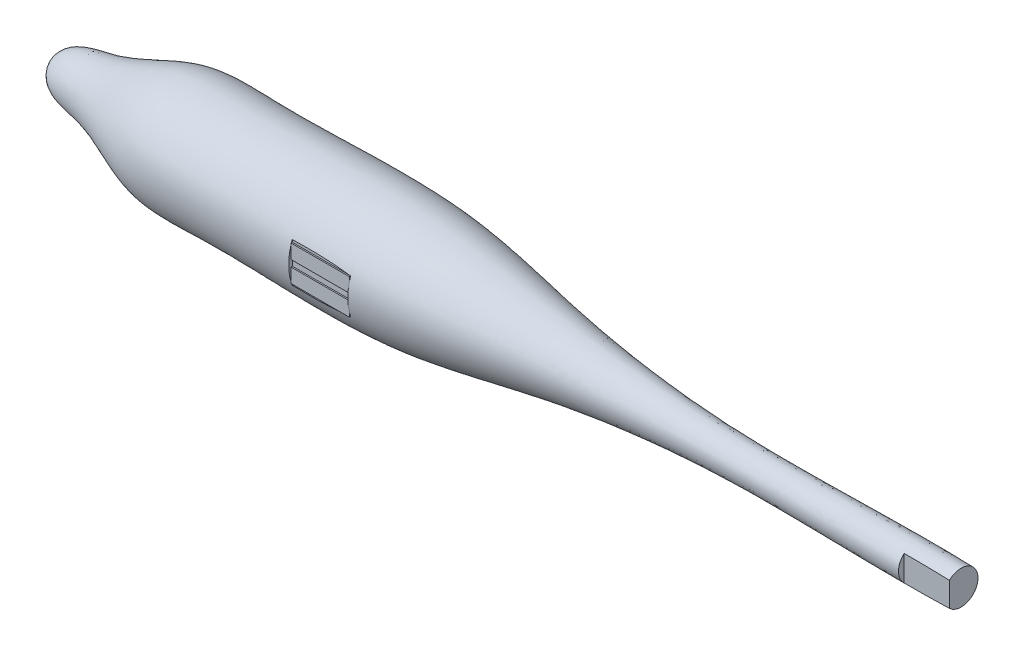
SolidWorks part; units mm, degrees
ref_plane "Front Plane" through (0, 0, 0) normal (0, 0, 1) x (1, 0, 0)
ref_plane "Top Plane" through (0, 0, 0) normal (0, 1, 0) x (1, 0, 0)
ref_plane "Right Plane" through (0, 0, 0) normal (1, 0, 0) x (0, 0, -1)
sketch "Sketch1" plane through (0, 0, 0) normal (0, 0, 1) x (1, 0, 0)
  line L1 (1400, 97.6339) -> (0, 97.6339) construction
  line L3 (0, 0) -> (1400, 0) construction
  line L5 (0, 0) -> (1400, 0)
  line L6 (1400, 0) -> (1400, 25.997)
  spline S0 degree 3 poles (0, 0) (6.0079, 35.1205) (87.5704, 35.98) (174.2855, 89.8849) (355.2298, 80.4635) (551.199, 98.1903) (802.5668, 43.0656) (1072.4121, 17.7479) (1281.1497, 28.8593) (1400, 25.997) knots 0 0 0 0 0.060909 0.147322 0.213189 0.431417 0.561861 0.75012 1 1 1 1
  dimension "D1" = 97.6339
revolve "Revolve2" add sketch "Sketch1" angle 360 about L5
ref_plane "Plane1" through (0, 0, 88) normal (0, 0, 1) x (1, 0, 0)
sketch "Sketch5" plane through (0, 0, 88) normal (0, 0, 1) x (1, 0, 0)
  line L0 (0, 0) -> (1400, 0) construction
  line L1 (450, 100) -> (540, 100)
  line L2 (450, 100) -> (450, -100)
  line L3 (450, -100) -> (540, -100)
  line L4 (540, 100) -> (540, -100)
  line L5 (450, 100) -> (540, -100) construction
  line L6 (450, -100) -> (540, 100) construction
  line L7 (1400, -25.997) -> (1400, 25.997) construction
  point P0 (495, 0)
  point P10 (0, 0)
  dimension "D1" = 450
  dimension "D2" = 90
  dimension "D3" = 200
sketch "Sketch7" plane through (0, 0, 88) normal (0, 0, 1) x (1, 0, 0)
  line L1 (1330.1015, 25) -> (1400.1015, 25)
  line L2 (1330.1015, 25) -> (1330.1015, -25)
  line L3 (1330.1015, -25) -> (1400.1015, -25)
  line L4 (1400.1015, 25) -> (1400.1015, -25)
  line L5 (1330.1015, 25) -> (1400.1015, -25) construction
  line L6 (1330.1015, -25) -> (1400.1015, 25) construction
  point P0 (1365.1015, 0)
extrude "Cut-Extrude3" cut sketch "Sketch7" against normal blind 70
extrude "Cut-Extrude4" cut sketch "Sketch5" against normal blind 6.5
sketch "Sketch8" plane through (0, 0, 81.5) normal (0, 0, 1) x (1, 0, 0)
  line L0 (450, 0) -> (540, 0) construction
  line L1 (450, 30.5883) -> (450, -30.5883) construction
  line L2 (540, 27.0452) -> (540, -27.0452) construction
  line L3 (540, -27.0452) -> (540, 27.0452) construction
  line L4 (450, 5) -> (540, 5)
  line L5 (450, 5) -> (450, -5)
  line L6 (450, -5) -> (540, -5)
  line L7 (540, 5) -> (540, -5)
  line L8 (450, 5) -> (540, -5) construction
  line L9 (450, -5) -> (540, 5) construction
  line L11 (540, -27.0452) -> (450, -27.0452)
  line L12 (540, -27.0452) -> (540, -5)
  line L13 (540, -5) -> (450, -5)
  line L14 (450, -27.0452) -> (450, -5)
  line L15 (540, 27.0452) -> (450, 27.0452)
  line L16 (540, 27.0452) -> (540, 5)
  line L17 (540, 5) -> (450, 5)
  line L18 (450, 27.0452) -> (450, 5)
  point P6 (495, 0)
  line M2 (450, 30.5883) -> (450, -30.5883)
  line M4 (540, -27.0452) -> (540, 27.0452)
  dimension "D1" = 10
  dimension "D2" = 22.0452
extrude "Boss-Extrude1" add sketch "Sketch8" along normal blind 2 contours L15 L4 M4 M2 | L11 L6 M4 M2
